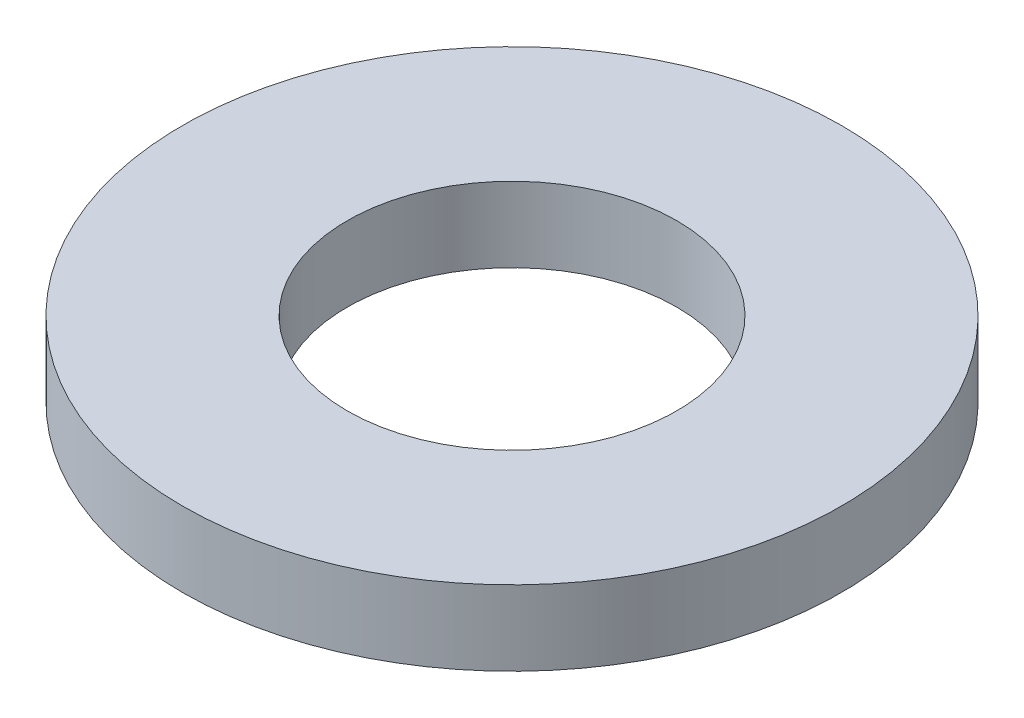
SolidWorks part; units mm, degrees
other "Markup1"
sketch "Sketch2" plane through (110, 12.5, -110) normal (0.5833, 0.4503, -0.676) x (-0.6693, -0.2051, -0.7141)
other "Markup2"
sketch "Sketch3" plane through (-110, 12.5, 110) normal (-0.1704, 0.536, 0.8269) x (0.9115, -0.2331, 0.339)
material "FeSr"
ref_plane "Front Plane" through (0, 0, 0) normal (0, 0, 1) x (1, 0, 0)
ref_plane "Top Plane" through (0, 0, 0) normal (0, 1, 0) x (1, 0, 0)
ref_plane "Right Plane" through (0, 0, 0) normal (1, 0, 0) x (0, 0, -1)
sketch "Sketch1" plane through (0, 0, 0) normal (0, 1, 0) x (1, 0, 0)
  circle A0 centre (0, 0) radius 55
  circle A1 centre (0, 0) radius 110
extrude "Boss-Extrude1" add sketch "Sketch1" along normal mid plane 25
